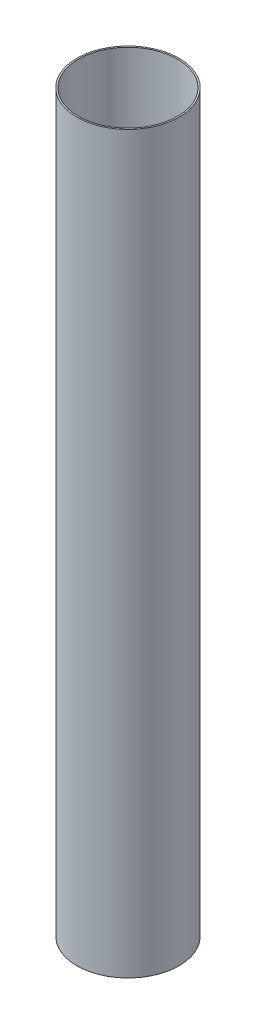
SolidWorks part; units mm, degrees
ref_plane "Front Plane" through (0, 0, 0) normal (0, 0, 1) x (1, 0, 0)
ref_plane "Top Plane" through (0, 0, 0) normal (0, 1, 0) x (1, 0, 0)
ref_plane "Right Plane" through (0, 0, 0) normal (1, 0, 0) x (0, 0, -1)
sketch "Sketch1" plane through (0, 0, 0) normal (0, 1, 0) x (1, 0, 0)
  circle A0 centre (0, 0) radius 32.5
  circle A1 centre (0, 0) radius 33.5
  dimension "D1" = 65
  dimension "D2" = 1
extrude "Boss-Extrude1" add sketch "Sketch1" along normal blind 482
